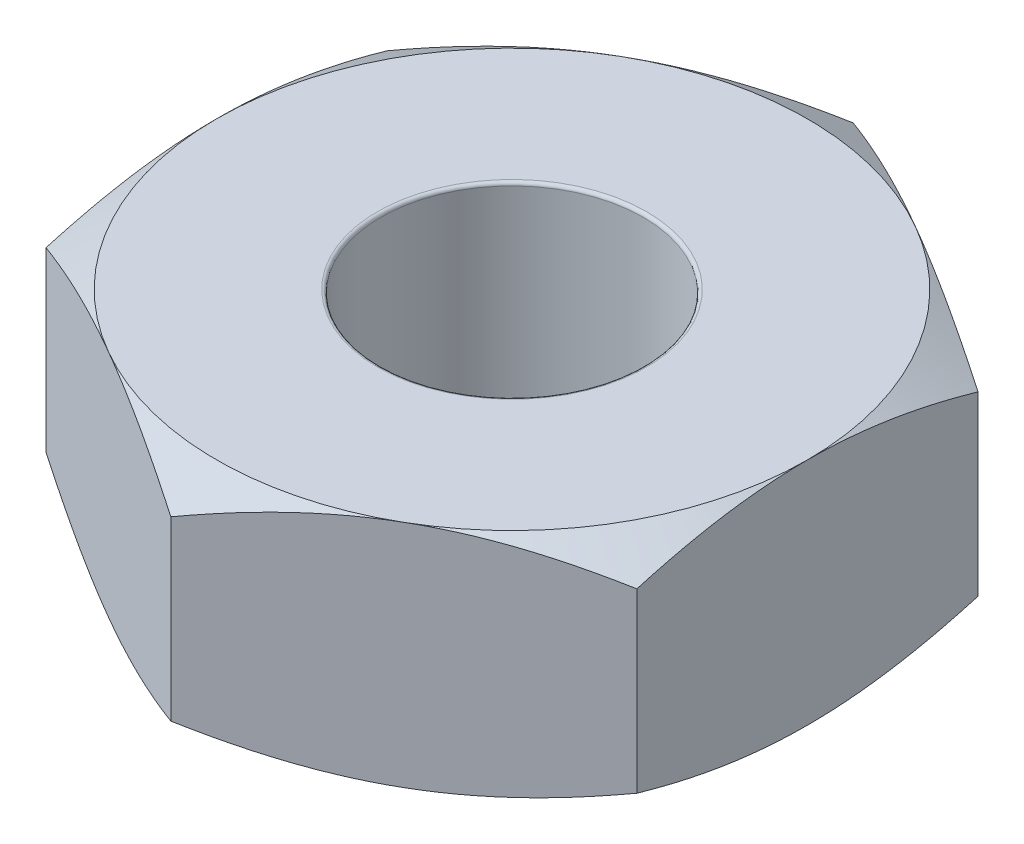
SolidWorks part; units mm, degrees
ref_plane "Front Plane" through (0, 0, 0) normal (0, 0, 1) x (1, 0, 0)
ref_plane "Top Plane" through (0, 0, 0) normal (0, 1, 0) x (1, 0, 0)
ref_plane "Right Plane" through (0, 0, 0) normal (1, 0, 0) x (0, 0, -1)
sketch "Sketch1" plane through (0, 0, 0) normal (0, 1, 0) x (1, 0, 0)
  line L1 (0, -2.5981) -> (2.25, -1.299)
  line L2 (2.25, -1.299) -> (2.25, 1.299)
  line L3 (2.25, 1.299) -> (0, 2.5981)
  line L4 (0, 2.5981) -> (-2.25, 1.299)
  line L5 (-2.25, 1.299) -> (-2.25, -1.299)
  line L6 (-2.25, -1.299) -> (0, -2.5981)
  circle A0 centre (0, 0) radius 1
  circle A1 centre (0, 0) radius 2.25 construction
  dimension "D1" = 2
  dimension "D2" = 4.5
extrude "Boss-Extrude1" add sketch "Sketch1" along normal blind 1.75
sketch "Sketch2" plane through (0, 1.75, 0) normal (0, 1, 0) x (1, 0, 0)
  circle A0 centre (0, 0) radius 2.25 construction
  circle A1 centre (0, 0) radius 2.25
extrude "Cut-Extrude1" cut sketch "Sketch2" against normal blind 1.75 draft 60 flip side to cut
sketch "Sketch3" plane through (0, 0, 0) normal (0, -1, 0) x (1, 0, 0)
  circle A0 centre (0, 0) radius 2.25 construction
  circle A1 centre (0, 0) radius 2.25
extrude "Cut-Extrude2" cut sketch "Sketch3" against normal blind 1.75 draft 60 flip side to cut
fillet "Fillet1" radius 0.025 2 edges at (0, 0, 1) (0, 1.75, 1)
